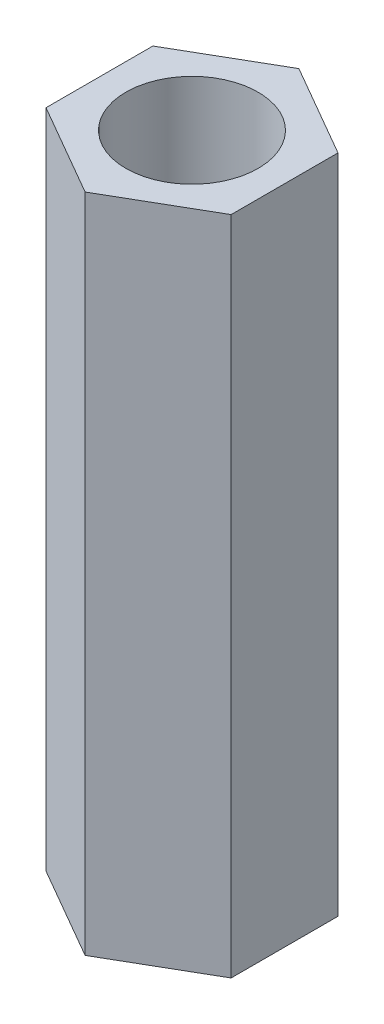
SolidWorks part; units mm, degrees
material "黄铜"
ref_plane "前视基准面" through (0, 0, 0) normal (0, 0, 1) x (1, 0, 0)
ref_plane "上视基准面" through (0, 0, 0) normal (0, 1, 0) x (1, 0, 0)
ref_plane "右视基准面" through (0, 0, 0) normal (1, 0, 0) x (0, 0, -1)
other "Configuration Table"
sketch "草图1" plane through (0, 0, 0) normal (0, 1, 0) x (1, 0, 0)
  line L1 (0, 1.6166) -> (-1.4, 0.8083)
  line L2 (-1.4, 0.8083) -> (-1.4, -0.8083)
  line L3 (-1.4, -0.8083) -> (0, -1.6166)
  line L4 (0, -1.6166) -> (1.4, -0.8083)
  line L5 (1.4, -0.8083) -> (1.4, 0.8083)
  line L6 (1.4, 0.8083) -> (0, 1.6166)
  circle A0 centre (0, 0) radius 1
  circle A1 centre (0, 0) radius 1.4 construction
  dimension "D1" = 2
  dimension "D2" = 2.8
extrude "凸台-拉伸1" add sketch "草图1" along normal blind 10
